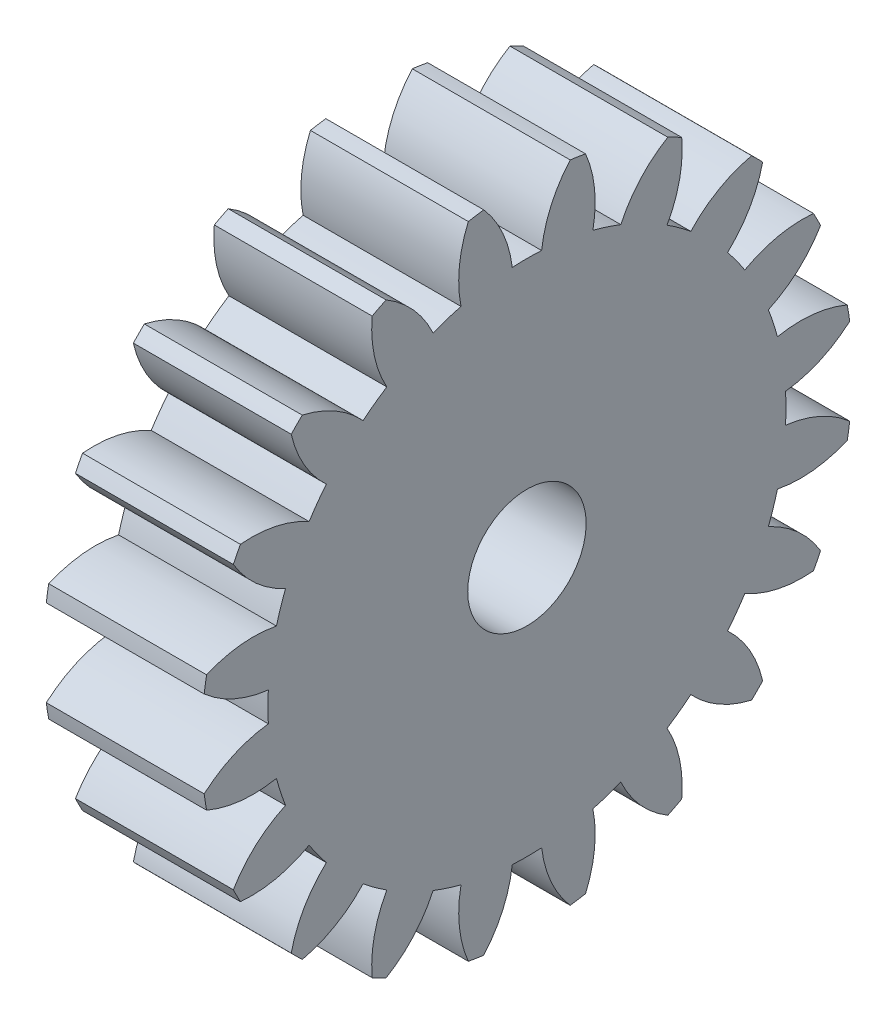
SolidWorks part; units mm, degrees
ref_plane "Plane1" through (0, 0, 0) normal (0, 0, 1) x (1, 0, 0)
ref_plane "Plane2" through (0, 0, 0) normal (0, 1, 0) x (1, 0, 0)
ref_plane "Plane3" through (0, 0, 0) normal (1, 0, 0) x (0, 0, -1)
sketch "HoldingSke" plane through (0, 0, 0) normal (0, 1, 0) x (1, 0, 0)
  line L0 (0, 0) -> (0.6265, -0.228)
  line L1 (-15, 0) -> (100, 0) construction
  line L2 (0, 0) -> (-2.1039, 2.3779)
  line L3 (0, 0) -> (-11.863, 4.5341)
  line L4 (0, 0) -> (8.1152, 2.9537)
  line L5 (0, 0) -> (-46.8476, -17.4728)
  line L6 (0, 0) -> (-6.6317, -4.4744)
  line L7 (-2.1039, 2.3779) -> (8.6586, 51.2059)
  line L8 (-76.2, 54.61) -> (-75.2, 54.61)
  line L9 (-71.009, 38.7566) -> (-53.1078, 45.2721)
  line L10 (-76.2, 71.12) -> (104.1128, 71.12)
  line L11 (0, 0) -> (-8, 0)
  line L12 (-76.2, 101.6) -> (-76.147, 101.6)
  line L13 (24.9733, 27.94) -> (52.9518, 28.4284)
  line L14 (24.9733, 27.94) -> (24.9743, 27.94)
  line L15 (24.9733, 27.94) -> (100.4006, 29.5858)
  line L16 (-63.627, -1.5) -> (-12.827, -1.5)
  circle A0 centre (0, 0) radius 3
  circle A1 centre (0, 0) radius 13.124
  circle A2 centre (0, 0) radius 37.5
  circle A3 centre (0, 0) radius 3
  dimension "MHD" = 26.248
  dimension "Hub_dia" = 75
  dimension "Bore" = 6
  dimension "MBD" = 6
  dimension "Num_teeth" = 20
  dimension "Pitch" = 0.6667
  dimension "Overall_len" = 50
  dimension "Show_teeth" = 20
  dimension "Thickness" = 8
  dimension "OAL" = 50.0001
  dimension "T_dim" = 1
  dimension "Ap" = 20
  dimension "H" = 19.05
  dimension "Pitch_radius" = 180.3128
  dimension "Width" = 8
  dimension "Backlash" = 0.053
  dimension "Addendum_fac" = 1
  dimension "Dedendum_fac" = 1.25
  dimension "Clearance_fac" = 0.25
  dimension "Dedendum_add" = 0.001
  dimension "Module" = 1.5
sketch "BasProSke" plane through (0, 0, 0) normal (0, 1, 0) x (1, 0, 0)
  line L0 (-10, 0) -> (60, 0) construction
  line L1 (0, 0) -> (0, 16.5)
  line L2 (0, 0) -> (8, 0)
  line L3 (8, 0) -> (8, 16.5)
  line L4 (8, 16.5) -> (0, 16.5)
  dimension "Thickness" = 8
  dimension "Diameter" = 33
revolve "Base-Revolve" add sketch "BasProSke" angle 360 about L0
sketch "TooCutSke" plane through (0, 0, 0) normal (1, 0, 0) x (0, 0, -1)
  line L1 (0, 0) -> (0, 107) construction
  line L2 (0, 0) -> (-1.2696, 14.9462) construction
  line L3 (0, 0) -> (-4.6808, 29.5532) construction
  line L4 (-1.2696, 14.9462) -> (-2.3404, 14.7766) construction
  arc A0 (0.7438, 13.1029) -> (-0.7438, 13.1029) centre (0, 0) ccw
  arc A1 (2.21, 16.377) -> (-2.21, 16.377) centre (0, 0) ccw
  circle A2 centre (0, 0) radius 15 construction
  circle A3 centre (0, 0) radius 14.0954 construction
  arc A4 (-0.7438, 13.1029) -> (-2.21, 16.377) centre (-6.7025, 12.3999) ccw
  arc A5 (2.21, 16.377) -> (0.7438, 13.1029) centre (6.7025, 12.3999) ccw
  dimension "Root_dia" = 26.248
  dimension "Overcut_dia" = 33.0508
  dimension "Pitch_dia" = 30
  dimension "Base_dia" = 28.1908
  dimension "Flank_rad" = 6
  dimension "Half_ang" = 9
  dimension "Half_CT" = 1.0841
extrude "ToothCut" cut sketch "TooCutSke" along normal through all
fillet "Breaks" [suppressed] radius 0.03
fillet "RootFillets" [suppressed] radius 0.376
pattern_circular "TeethCuts" count 20 every 18 about axis through (-10, 0, 0) along (1, 0, 0) of "ToothCut", "RootFillets", "Breaks"
sketch "HubNeaOneSke" plane through (0, 0, 0) normal (-1, 0, 0) x (0, 0, 1)
  circle A0 centre (0, 0) radius 13.124
  dimension "Diameter" = 26.248
extrude "HubNearOne" [suppressed] add sketch "HubNeaOneSke" along normal blind 42.0001
sketch "HubNeaBotSke" plane through (0, 0, 0) normal (-1, 0, 0) x (0, 0, 1)
  circle A0 centre (0, 0) radius 13.124
  dimension "Diameter" = 26.248
extrude "HubNearBoth" [suppressed] add sketch "HubNeaBotSke" along normal blind 21
ref_plane "FarPln" through (8, 0, 0) normal (1, 0, 0) x (0, 0, -1)
sketch "HubFarSke" plane through (8, 0, 0) normal (1, 0, 0) x (0, 0, -1)
  circle A0 centre (0, 0) radius 13.124
  dimension "Diameter" = 26.248
extrude "HubFar" [suppressed] add sketch "HubFarSke" along normal blind 21
sketch "BorSke" plane through (0, 0, 0) normal (1, 0, 0) x (0, 0, -1)
  circle A0 centre (0, 0) radius 3
  dimension "Diameter" = 6
extrude "Bore" cut sketch "BorSke" along normal mid plane 100.0001
sketch "KeySke" plane through (0, 0, 0) normal (1, 0, 0) x (0, 0, -1)
  line L0 (-1, 0) -> (-1, 4)
  line L1 (-1, 4) -> (1, 4)
  line L2 (1, 4) -> (1, 0)
  line L3 (0, 0) -> (0, 34) construction
  line L4 (-1, 0) -> (1, 0)
  dimension "Offset" = 4
  dimension "Width" = 2
extrude "Keyway" [suppressed] cut sketch "KeySke" along normal mid plane 100.0001
pattern_circular "Keyway2" [suppressed] count 2 every 90 about axis through (-10, 0, 0) along (1, 0, 0)
equation "' \"Module@HoldingSke\" = 6.35"
equation "' \"Num_teeth@HoldingSke\" = 12"
equation "' \"Ap@HoldingSke\" =  20"
equation "' \"Ap@HoldingSke\" = 20"
equation "' \"Width@HoldingSke\" = 0.5 * 25.4"
equation "' \"Hub_dia@HoldingSke\"= 1 * 25.4"
equation "' \"Hub_dia@HoldingSke\" = 1 * 25.4"
equation "' \"Overall_len@HoldingSke\" = 1.0 * 25.4"
equation "' \"Bore@HoldingSke\" = 0.75 * 25.4"
equation "' \"T_dim@HoldingSke\" = 0.1 * 25.4"
equation "' \"Width@KeySke\" = 0.25 * 25.4"
equation "' \"Show_teeth@HoldingSke\" = 13"
equation "' \"Backlash@HoldingSke\" = 0.009 * 25.4"
equation "' \"Addendum_fac@HoldingSke\" = 1.0"
equation "' \"Dedendum_fac@HoldingSke\" = 1.25"
equation "' \"Dedendum_add@HoldingSke\" = 0.00005 * 25.4"
equation "' \"Clearance_fac@HoldingSke\" = 0.25"
equation "\"Pitch@HoldingSke\" = 1 / \"Module@HoldingSke\""
equation "\"Overcut_dia@TooCutSke\" = (\"Num_teeth@HoldingSke\" + 2 * \"Addendum_fac@HoldingSke\") / \"Pitch@HoldingSke\" + 0.002 * 25.4"
equation "\"Pitch_dia@TooCutSke\" = \"Num_teeth@HoldingSke\" / \"Pitch@HoldingSke\""
equation "\"Base_dia@TooCutSke\" = \"Num_teeth@HoldingSke\" / \"Pitch@HoldingSke\" * cos((\"Ap@HoldingSke\"  * 3.14159265 / 180))"
equation "\"Root_dia@TooCutSke\" = (\"Num_teeth@HoldingSke\" + 2) / \"Pitch@HoldingSke\" - 2 * (\"Addendum_fac@HoldingSke\" + \"Dedendum_fac@HoldingSke\") / \"Pitch@HoldingSke\" - \"Dedendum_add@HoldingSke\" * 2"
equation "\"Half_ang@TooCutSke\" = 180 / \"Num_teeth@HoldingSke\""
equation "\"Half_CT@TooCutSke\" = \"Num_teeth@HoldingSke\" / \"Pitch@HoldingSke\" * sin((3.14159265 / 2 / \"Num_teeth@HoldingSke\")) / 2 - 7 * \"Backlash@HoldingSke\" / 4"
equation "\"Flank_rad@TooCutSke\" = \"Num_teeth@HoldingSke\" / \"Pitch@HoldingSke\" / 5"
equation "\"Radius@RootFillets\" = \"Clearance_fac@HoldingSke\" / \"Pitch@HoldingSke\" + \"Dedendum_add@HoldingSke\""
equation "\"Break_rad@Breaks\" = 0.02 / \"Pitch@HoldingSke\""
equation "\"Thickness@HoldingSke\" = \"Width@HoldingSke\""
equation "\"OAL@HoldingSke\" = \"Thickness@HoldingSke\""
equation "\"MHD@HoldingSke\" = (\"Num_teeth@HoldingSke\" + 2) / \"Pitch@HoldingSke\" - 2 * (\"Addendum_fac@HoldingSke\" + \"Dedendum_fac@HoldingSke\")  / \"Pitch@HoldingSke\" - \"Dedendum_add@HoldingSke\" * 2"
equation "\"MBD@HoldingSke\" = (\"Num_teeth@HoldingSke\" + 2) / \"Pitch@HoldingSke\" - 2 * (\"Addendum_fac@HoldingSke\" + \"Dedendum_fac@HoldingSke\")  / \"Pitch@HoldingSke\" - \"Dedendum_add@HoldingSke\" * 2 - 0.002 * 25.4"
equation "\"MHD@HoldingSke\" = ((sgn( \"MHD@HoldingSke\" - \"Hub_dia@HoldingSke\" )-1)*( \"MHD@HoldingSke\" - \"Hub_dia@HoldingSke\" ))/-2+ \"Hub_dia@HoldingSke\""
equation "\"MBD@HoldingSke\" = ((sgn( \"MBD@HoldingSke\" - \"Bore@HoldingSke\" )-1)*( \"MBD@HoldingSke\" - \"Bore@HoldingSke\" ))/-2+ \"Bore@HoldingSke\""
equation "\"OAL@HoldingSke\" = ((sgn( \"OAL@HoldingSke\" - \"Overall_len@HoldingSke\" )+1)*( \"OAL@HoldingSke\" - \"Overall_len@HoldingSke\" ))/2 + \"Overall_len@HoldingSke\" + 0.000002 * 25.4"
equation "\"Num_teeth@TeethCuts\" = int( \"Show_teeth@HoldingSke\" ) + 1"
equation "\"Num_teeth@TeethCuts\" = ((sgn( \"Num_teeth@TeethCuts\" - \"Num_teeth@HoldingSke\" )-1)*( \"Num_teeth@TeethCuts\" - \"Num_teeth@HoldingSke\" ))/-2+ \"Num_teeth@HoldingSke\""
equation "\"Num_teeth@TeethCuts\" = ((sgn( \"Num_teeth@TeethCuts\" - 2.0)+1)*( \"Num_teeth@TeethCuts\" - 2.0))/2 +2.0"
equation "\"Angle@TeethCuts\" = 360.0 / \"Num_teeth@HoldingSke\""
equation "\"Diameter@BasProSke\" = (\"Num_teeth@HoldingSke\" + 2 * \"Addendum_fac@HoldingSke\") / \"Pitch@HoldingSke\""
equation "\"Thickness@BasProSke\"  = \"Thickness@HoldingSke\""
equation "' \"Fillet_rad@BasProSke\" =  \"Thickness@HoldingSke\" * 0.05"
equation "' \"Fillet_rad@BasProSke\" = \"Thickness@HoldingSke\" * 0.05"
equation "\"MHD@HoldingSke\" = ((sgn( \"MHD@HoldingSke\" - \"Root_dia@TooCutSke\" )-1)*( \"MHD@HoldingSke\" - \"Root_dia@TooCutSke\" ))/-2+ \"Root_dia@TooCutSke\""
equation "\"Diameter@HubNeaOneSke\" = \"MHD@HoldingSke\""
equation "\"Length@HubNearOne\" = \"OAL@HoldingSke\" - \"Thickness@BasProSke\""
equation "\"Diameter@HubNeaBotSke\" = \"MHD@HoldingSke\""
equation "\"Length@HubNearBoth\" = ( \"OAL@HoldingSke\" - \"Thickness@BasProSke\" ) / 2.0"
equation "\"Thickness@FarPln\" = \"Thickness@BasProSke\""
equation "\"Diameter@HubFarSke\" = \"MHD@HoldingSke\""
equation "\"Length@HubFar\" = ( \"OAL@HoldingSke\" - \"Thickness@BasProSke\" ) / 2.0"
equation "\"Diameter@BorSke\" = \"MBD@HoldingSke\""
equation "\"D1@Bore\" = \"OAL@HoldingSke\" * 2.0"
equation "\"D1@Keyway\" = \"OAL@HoldingSke\" * 2.0"
equation "\"Offset@KeySke\" = \"T_dim@HoldingSke\" + \"MBD@HoldingSke\" / 2.0"
